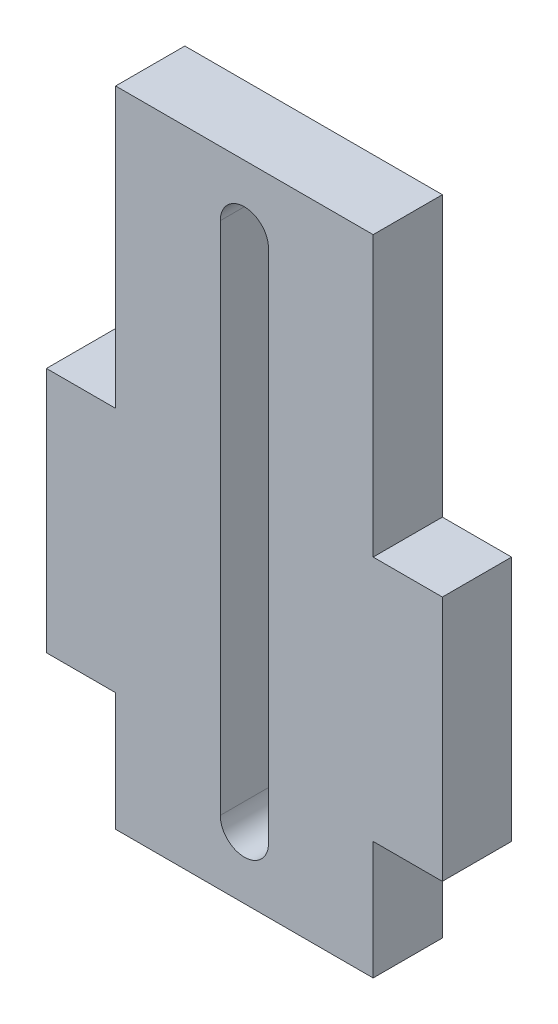
SolidWorks part; units mm, degrees
ref_plane "Front Plane" through (0, 0, 0) normal (0, 0, 1) x (1, 0, 0)
ref_plane "Top Plane" through (0, 0, 0) normal (0, 1, 0) x (1, 0, 0)
ref_plane "Right Plane" through (0, 0, 0) normal (1, 0, 0) x (0, 0, -1)
sketch "Sketch1" plane through (0, 0, 0) normal (0, 0, 1) x (1, 0, 0)
  line L0 (-8, 2.65) -> (-8, 20)
  line L1 (-8, -20) -> (8, -20)
  line L2 (-8, -20) -> (-8, -12.65)
  line L3 (-8, 20) -> (8, 20)
  line L4 (8, -20) -> (8, -12.65)
  line L5 (-8, -20) -> (8, 20) construction
  line L6 (-8, 20) -> (8, -20) construction
  line L7 (8, -12.65) -> (12.3, -12.65)
  line L9 (8, 2.65) -> (12.3, 2.65)
  line L10 (12.3, -12.65) -> (12.3, 2.65)
  line L11 (-8, 2.65) -> (-12.3, 2.65)
  line L13 (-8, -12.65) -> (-12.3, -12.65)
  line L14 (-12.3, 2.65) -> (-12.3, -12.65)
  line L15 (8, 2.65) -> (8, 20)
  line L16 (-1.5, -16) -> (-1.5, 16)
  line L17 (1.5, 16) -> (1.5, -16)
  arc A0 (-1.5, -16) -> (1.5, -16) centre (0, -16) ccw
  arc A1 (1.5, 16) -> (-1.5, 16) centre (0, 16) ccw
  point P0 (0, 0)
  point P14 (12.3, -5)
  point P15 (-12.3, -5)
  dimension "D9" = 3
  dimension "D1" = 16
  dimension "D2" = 40
  dimension "D3" = 15.3
  dimension "D4" = 15.3
  dimension "D5" = 4.3
  dimension "D6" = 4.3
  dimension "D7" = 25
  dimension "D8" = 25
  dimension "D10" = 4
  dimension "D11" = 4
extrude "Boss-Extrude1" add sketch "Sketch1" along normal blind 4.3
